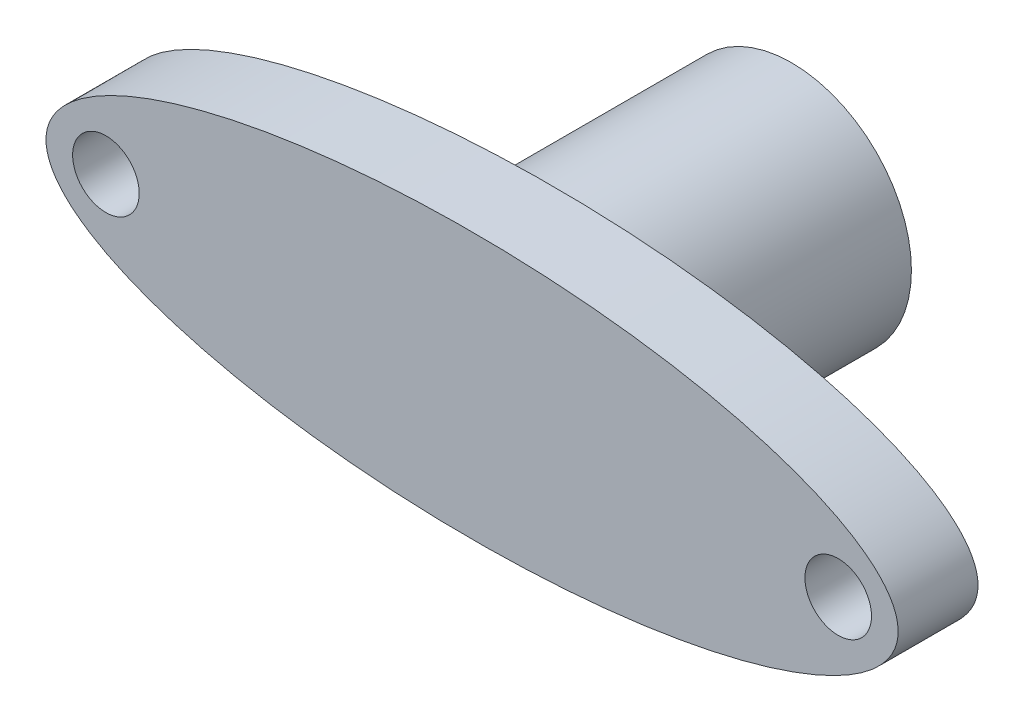
SolidWorks part; units mm, degrees
material "ABS PC"
ref_plane "Front Plane" through (0, 0, 0) normal (0, 0, 1) x (1, 0, 0)
ref_plane "Top Plane" through (0, 0, 0) normal (0, 1, 0) x (1, 0, 0)
ref_plane "Right Plane" through (0, 0, 0) normal (1, 0, 0) x (0, 0, -1)
sketch "Sketch1" plane through (0, 0, 0) normal (0, 0, 1) x (1, 0, 0)
  circle A0 centre (-1619.3321, 736.1661) radius 62.5
  circle A1 centre (-244.3321, 736.1661) radius 62.5
  ellipse E1 centre (-931.8321, 736.1661) end of major axis (-131.8321, 736.1661) minor radius 250
extrude "Boss-Extrude1" add sketch "Sketch1" along normal blind 150 contours E1 | A0 | A1
sketch "Sketch3" plane through (0, 0, 0) normal (0, 0, 1) x (1, 0, 0)
  circle A0 centre (-931.8321, 736.1661) radius 225
sketch "Sketch12" plane through (0, 0, 0) normal (0, 0, -1) x (-1, 0, 0)
  line L1 (991.0872, 633.9243) -> (1050.0037, 736.3616)
  line L2 (1050.0037, 736.3616) -> (990.7486, 838.6034)
  line L3 (990.7486, 838.6034) -> (872.5771, 838.4079)
  line L4 (872.5771, 838.4079) -> (813.6606, 735.9706)
  line L5 (813.6606, 735.9706) -> (872.9157, 633.7288)
  line L6 (872.9157, 633.7288) -> (991.0872, 633.9243)
  circle A0 centre (931.8321, 736.1661) radius 102.3397 construction
  point P11 (0, 0)
  point P12 (991.9394, 639.4021)
  point P13 (0, 0)
  point P14 (991.219, 648.0037)
  point P15 (990.7486, 633.9243)
extrude "Boss-Extrude9" add sketch "Sketch12" along normal blind 150
sketch "Sketch15" plane through (0, 0, -150) normal (0, 0, -1) x (-1, 0, 0)
  line L1 (1050.0037, 736.3616) -> (990.7486, 838.6034)
  line L2 (990.7486, 838.6034) -> (872.5771, 838.4079)
  line L3 (872.5771, 838.4079) -> (813.6606, 735.9706)
  line L4 (813.6606, 735.9706) -> (872.9157, 633.7288)
  line L5 (872.9157, 633.7288) -> (991.0872, 633.9243)
  line L6 (991.0872, 633.9243) -> (1050.0037, 736.3616)
  circle A0 centre (931.8321, 736.1661) radius 102.3397 construction
sketch "Sketch16" plane through (0, 0, 0) normal (0, 0, -1) x (-1, 0, 0)
  circle A0 centre (931.8321, 736.1661) radius 225
sketch "Sketch17" plane through (0, 0, 0) normal (0, 0, -1) x (-1, 0, 0)
  line L1 (991.0872, 633.9243) -> (1050.0037, 736.3616)
  line L2 (1050.0037, 736.3616) -> (990.7486, 838.6034)
  line L3 (990.7486, 838.6034) -> (872.5771, 838.4079)
  line L4 (872.5771, 838.4079) -> (813.6606, 735.9706)
  line L5 (813.6606, 735.9706) -> (872.9157, 633.7288)
  line L6 (872.9157, 633.7288) -> (991.0872, 633.9243)
  circle A0 centre (931.8321, 736.1661) radius 102.3397 construction
  circle A1 centre (931.8321, 736.1661) radius 225
extrude "Boss-Extrude13" add sketch "Sketch17" along normal blind 450
